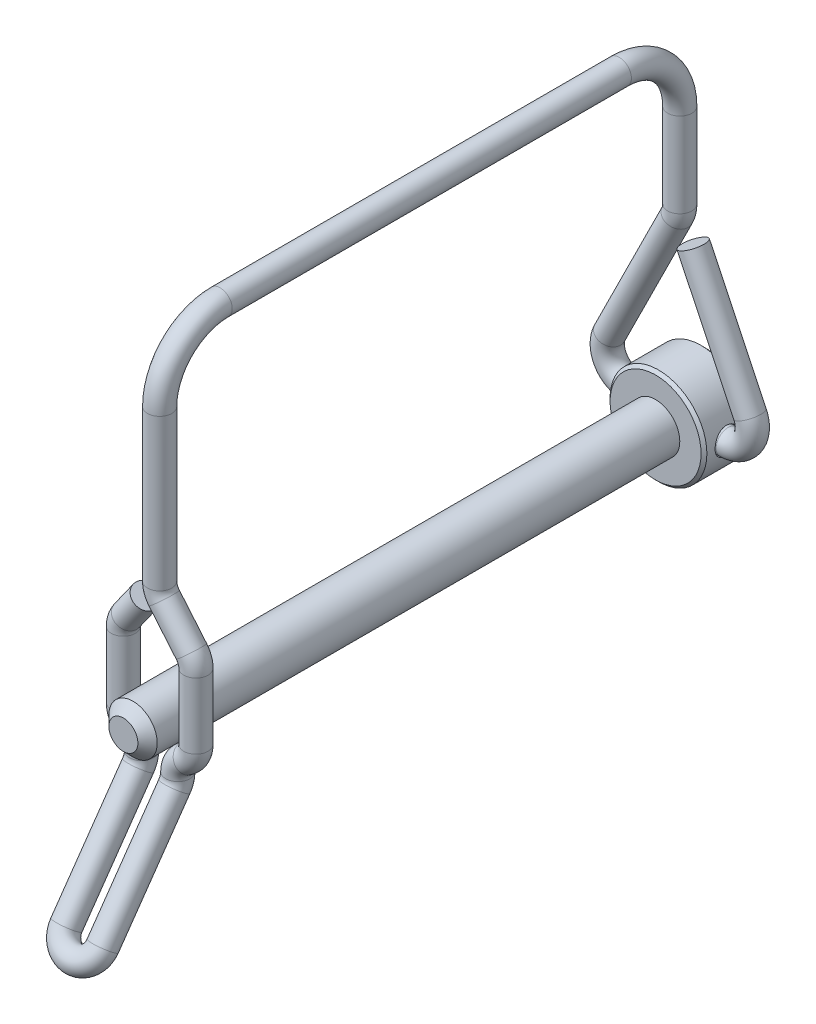
SolidWorks part; units mm, degrees
ref_plane "Front" through (0, 0, 0) normal (0, 0, 1) x (1, 0, 0)
ref_plane "Top" through (0, 0, 0) normal (0, 1, 0) x (1, 0, 0)
ref_plane "Right" through (0, 0, 0) normal (1, 0, 0) x (0, 0, -1)
sketch "Sketch1" plane through (0, 0, 0) normal (1, 0, 0) x (0, 0, -1)
  line L0 (-38.1, 0) -> (38.1, 0)
  line L1 (38.1, 0) -> (38.1, 5.969)
  line L2 (37.719, 6.35) -> (32.131, 6.35)
  line L3 (31.75, 5.969) -> (31.75, 3.175)
  line L4 (31.75, 3.175) -> (-36.83, 3.175)
  line L5 (-38.1, 1.905) -> (-38.1, 0)
  line L6 (0, 0) -> (0, 3.175) construction
  line L7 (0, 0) -> (0, -3.175) construction
  line L8 (34.925, 6.35) -> (34.925, 0) construction
  line L9 (34.925, 0) -> (34.925, -6.35) construction
  line L10 (-36.83, 3.175) -> (-38.1, 1.905)
  line L11 (32.131, 6.35) -> (31.75, 5.969)
  line L12 (38.1, 5.969) -> (37.719, 6.35)
  line L13 (-38.1, 1.905) -> (-38.1, 3.175) construction
  line L14 (-38.1, 3.175) -> (-36.83, 3.175) construction
  point P4 (38.1, 6.35)
  point P5 (31.75, 6.35)
  point P7 (-38.1, 3.175)
  dimension "D2" = 12.7
  dimension "D3" = 6.35
  dimension "D4" = 69.85
  dimension "D5" = 1.27
revolve "Revolve1" add sketch "Sketch1" angle 360 mid plane about L0
sketch "Sketch2" plane through (0, 0, 0) normal (1, 0, 0) x (0, 0, -1)
  line L0 (31.75, 0) -> (38.1, 0) construction
  line L1 (31.75, 3.175) -> (31.75, -3.175) construction
  line L2 (38.1, -5.969) -> (38.1, 5.969) construction
  circle A0 centre (34.925, 0) radius 1.7145
  dimension "D1" = 3.429
extrude "Cut-Extrude1" cut sketch "Sketch2" against normal through all and the other way through all
sketch "Sketch3" plane through (0, 0, 0) normal (1, 0, 0) x (0, 0, -1)
  line L0 (34.925, 0) -> (34.925, 25.4) construction
  line L1 (34.925, 25.4) -> (34.925, 34.925)
  line L2 (26.9875, 42.8625) -> (-25.4, 42.8625)
  line L3 (-33.3375, 34.925) -> (-33.3375, 15.875)
  line L4 (37.719, 6.35) -> (32.131, 6.35) construction
  line L5 (0.7937, 44.45) -> (0.7937, 42.8625) construction
  line L6 (0.7937, 42.8625) -> (0.7937, 41.275) construction
  line L7 (31.75, 3.175) -> (-36.83, 3.175) construction
  line L8 (-34.925, 15.875) -> (-33.3375, 15.875) construction
  line L9 (-33.3375, 15.875) -> (-31.75, 15.875) construction
  line L10 (31.75, 5.969) -> (31.75, -5.969) construction
  line L11 (-33.3375, 15.875) -> (-33.3375, 3.175) construction
  line L12 (-36.83, 3.175) -> (-33.3375, 3.175) construction
  arc A0 (-25.4, 42.8625) -> (-33.3375, 34.925) centre (-25.4, 34.925) ccw
  arc A1 (34.925, 34.925) -> (26.9875, 42.8625) centre (26.9875, 34.925) ccw
  dimension "D6" = 7.9375
  dimension "D1" = 19.05
  dimension "D2" = 3.175
  dimension "D3" = 38.1
  dimension "D4" = 63.5
  dimension "D5" = 12.7
ref_plane "Plane1" through (0, 0, -34.925) normal (0, 0, 1) x (1, 0, 0)
sketch "Sketch4" plane through (0, 0, -34.925) normal (0, 0, 1) x (1, 0, 0)
  line L0 (-6.35, 0) -> (6.35, 0)
  line L1 (0, 25.4) -> (0, 23.8125)
  line L2 (-0.3324, 22.3982) -> (-9.1926, 4.5893)
  line L3 (9.2143, 4.5448) -> (1.7533, 20.1462)
  line L4 (1.7533, 20.1462) -> (0, 23.8125) construction
  arc A0 (-6.35, 0) -> (-9.1926, 4.5893) centre (-6.35, 3.175) cw
  arc A1 (6.35, 0) -> (9.2143, 4.5448) centre (6.35, 3.175) ccw
  arc A3 (0, 23.8125) -> (-0.3324, 22.3982) centre (-3.175, 23.8125) cw
  dimension "D1" = 3.175
  dimension "D2" = 12.7
  dimension "D3" = 3.175
  dimension "D4" = 1.5875
  dimension "D5" = 4.064
ref_plane "Plane2" through (0, 0, 33.3375) normal (0, 0, 1) x (1, 0, 0)
sketch "Sketch5" plane through (0, 0, 33.3375) normal (0, 0, 1) x (1, 0, 0)
  line L0 (0, 15.875) -> (0, 15.0812)
  line L1 (0.5942, 13.4486) -> (4.1683, 9.1892)
  line L2 (4.7625, 7.5566) -> (4.7625, -1.0913)
  line L3 (3.175, 0) -> (4.7625, 0) construction
  line L4 (0, 42.8625) -> (0, 41.275) construction
  line L5 (3.2095, -3.5186) -> (2.1397, -2.3457) construction
  line L6 (0, -1.0913) -> (4.7625, -1.0913) construction
  line L7 (0, -1.0913) -> (-4.7625, -1.0913) construction
  line L9 (0, -1.0913) -> (0, -5.3952) construction
  line L10 (-0.7937, -5.3952) -> (0.7937, -5.3952) construction
  line L11 (0.7937, -5.3952) -> (2.3812, -5.3952) construction
  line L12 (-2.3812, -5.3952) -> (-0.7937, -5.3952) construction
  circle A0 centre (0, 0) radius 3.175 construction
  circle A1 centre (0, 0) radius 3.175 construction
  arc A2 (4.1683, 9.1892) -> (4.7625, 7.5566) centre (2.2225, 7.5566) cw
  arc A3 (0, 15.0812) -> (0.5942, 13.4486) centre (2.54, 15.0812) ccw
  arc A4 (3.5719, -3.2432) -> (4.7625, -1.0913) centre (2.2225, -1.0913) ccw
  arc A5 (3.5719, -3.2432) -> (2.3812, -5.3952) centre (4.9212, -5.3952) ccw
  dimension "D1" = 2.54
  dimension "D2" = 0.7937
  dimension "D3" = 140
  dimension "D4" = 2.3812
ref_plane "Plane3" through (2.3812, 0, 0) normal (1, 0, 0) x (0, 0, -1)
sketch "Sketch6" plane through (2.3812, 0, 0) normal (1, 0, 0) x (0, 0, -1)
  line L0 (-33.3375, -5.3952) -> (-35.8775, -5.3952) construction
  line L1 (-33.7969, -6.852) -> (-43.1953, -20.2744)
  line L3 (-33.7969, -6.852) -> (-33.7969, -5.3952) construction
  line L4 (-43.1953, -20.2744) -> (-44.5611, -22.225) construction
  line L5 (-36.83, -3.175) -> (31.75, -3.175) construction
  arc A0 (-33.7969, -6.852) -> (-33.3375, -5.3952) centre (-35.8775, -5.3952) ccw
  dimension "D1" = 2.54
  dimension "D2" = 145
  dimension "D3" = 2.3813
  dimension "D4" = 19.05
sketch "Sketch7" plane through (0, 0, 33.3375) normal (0, 0, 1) x (1, 0, 0)
  line L0 (-4.7625, -1.0913) -> (-4.7625, 7.5566)
  line L1 (4.7625, 7.5566) -> (-4.7625, 7.5566) construction
  line L2 (-4.2944, 9.0259) -> (-1.8367, 12.4914)
  line L3 (-1.8367, 12.4914) -> (-0.9183, 13.7863) construction
  line L4 (-0.9183, 13.7863) -> (0, 15.0812) construction
  line L5 (0, 44.45) -> (0, 42.8625) construction
  line L6 (0, 15.0812) -> (0, 0) construction
  arc A0 (-4.2944, 9.0259) -> (-4.7625, 7.5566) centre (-2.2225, 7.5566) ccw
  arc A1 (4.7625, 7.5566) -> (4.1683, 9.1892) centre (2.2225, 7.5566) ccw construction
  arc A3 (3.5719, -3.2432) -> (2.3812, -5.3952) centre (4.9212, -5.3952) ccw construction
  arc A4 (3.5719, -3.2432) -> (4.7625, -1.0913) centre (2.2225, -1.0913) ccw construction
  arc A5 (3.5719, -3.2432) -> (2.3812, -5.3952) centre (4.9212, -5.3952) ccw construction
  arc A6 (3.5719, -3.2432) -> (4.7625, -1.0913) centre (2.2225, -1.0913) ccw construction
  arc A7 (-3.5719, -3.2432) -> (-2.3812, -5.3952) centre (-4.9212, -5.3952) cw
  arc A8 (-3.5719, -3.2432) -> (-4.7625, -1.0913) centre (-2.2225, -1.0913) cw
ref_plane "Plane4" through (-2.3812, 0, 0) normal (1, 0, 0) x (0, 0, -1)
sketch "Sketch8" plane through (-2.3812, 0, 0) normal (1, 0, 0) x (0, 0, -1)
  line L0 (-33.7969, -6.852) -> (-43.1953, -20.2744) construction
  line L1 (-33.7969, -6.852) -> (-43.1953, -20.2744)
  arc A0 (-33.7969, -6.852) -> (-33.3375, -5.3952) centre (-35.8775, -5.3952) ccw construction
  arc A1 (-33.7969, -6.852) -> (-33.3375, -5.3952) centre (-35.8775, -5.3952) ccw
ref_plane "Plane5" through (0, 13.6251, 19.4586) normal (0, 0.5736, 0.8192) x (1, 0, 0)
sketch "Sketch9" plane through (0, 13.6251, 19.4586) normal (0, 0.5736, 0.8192) x (1, 0, 0)
  line L0 (-2.3812, -41.3836) -> (2.3813, -41.3836) construction
  line L1 (-2.3812, -24.9979) -> (-2.3812, -41.3836) construction
  line L2 (2.3813, -41.3836) -> (2.3813, -43.7649) construction
  arc A0 (-2.3812, -41.3836) -> (2.3813, -41.3836) centre (0, -41.3836) ccw
ref_plane "Plane6" through (1.7533, 20.1462, -34.925) normal (-0.4314, 0.9021, 0) x (-0.9021, -0.4314, 0)
sketch "Sketch10" plane through (-19.2954, 10.0801, 0) normal (0.4314, -0.9021, 0) x (0, 0, -1)
  circle A0 centre (34.925, 23.3318) radius 1.5875
  dimension "D1" = 3.175
curve "CompCurve1"
sweep "Sweep1" add profiles "Sketch10" path "CompCurve1"
equation "\"D1@Sketch6\"=\"D1@Sketch5\""
equation "\"D3@Sketch6\"=\"D4@Sketch5\""
equation "\"D5@Sketch1\"=\"D1@Sketch1\"*.2"
